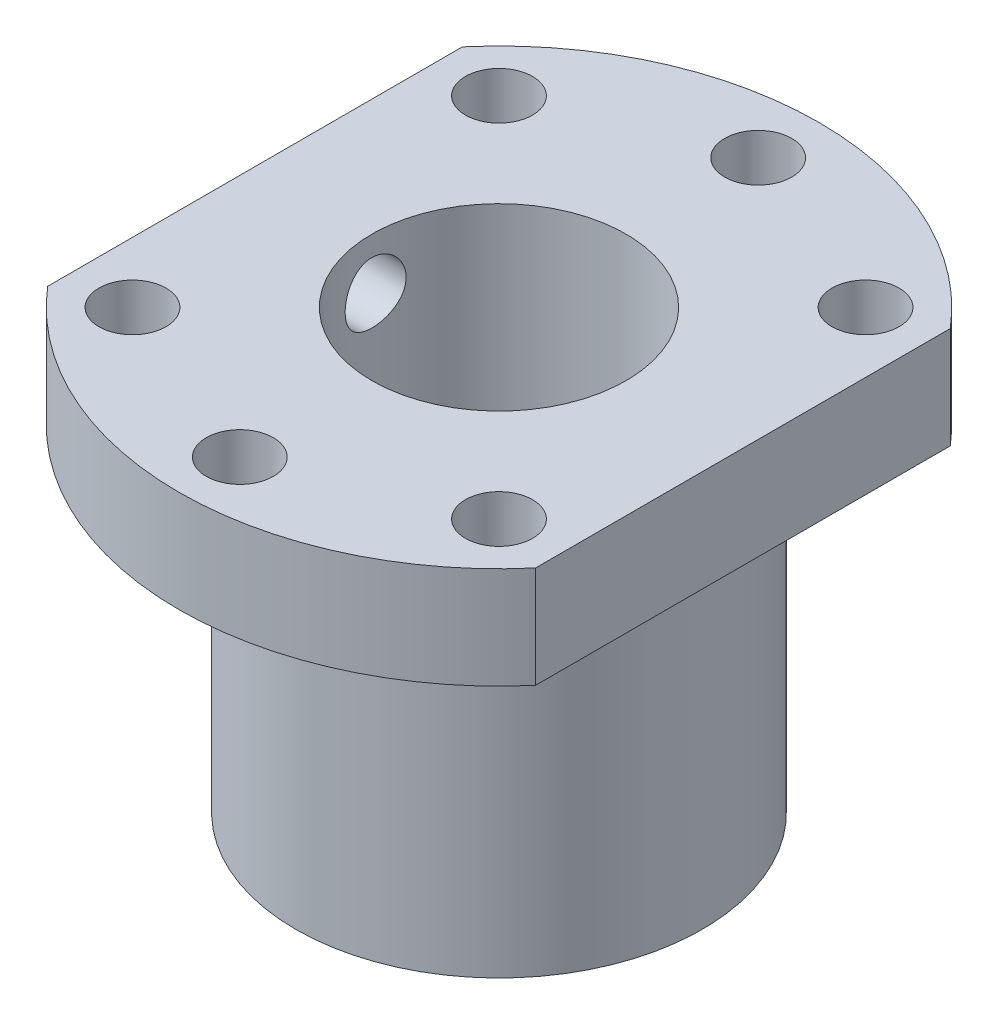
SolidWorks part; units mm, degrees
material "合金钢"
ref_plane "前视基准面" through (0, 0, 0) normal (0, 0, 1) x (1, 0, 0)
ref_plane "上视基准面" through (0, 0, 0) normal (0, 1, 0) x (1, 0, 0)
ref_plane "右视基准面" through (0, 0, 0) normal (1, 0, 0) x (0, 0, -1)
sketch "草图1" plane through (0, 0, 0) normal (0, 1, 0) x (1, 0, 0)
  line L0 (-24, 20.4022) -> (-24, -20.4022)
  line L1 (24, 20.4022) -> (24, -20.4022)
  arc A0 (24, 20.4022) -> (-24, 20.4022) centre (0, 0) ccw
  arc A1 (-24, -20.4022) -> (24, -20.4022) centre (0, 0) ccw
  circle A2 centre (0, 0) radius 12.5
  dimension "D1" = 63
  dimension "D3" = 25
  dimension "D2" = 48
extrude "凸台-拉伸1" add sketch "草图1" against normal blind 10
sketch "草图2" plane through (0, 0, 0) normal (0, 1, 0) x (1, 0, 0)
  circle A0 centre (0, 0) radius 20
  circle A1 centre (0, 0) radius 12.5
  dimension "D1" = 40
  dimension "D2" = 25
extrude "凸台-拉伸2" add sketch "草图2" against normal blind 43
sketch "草图3" plane through (0, 0, 0) normal (0, 1, 0) x (1, 0, 0)
  line L0 (-25.5, 0) -> (25.5, 0) construction
  line L1 (0, 0) -> (-18.0312, 18.0312) construction
  line L2 (0, 0) -> (18.0312, 18.0312) construction
  line L3 (0, 0) -> (0, 25.5) construction
  circle A0 centre (0, 0) radius 25.5 construction
  circle A1 centre (0, 25.5) radius 3.3
  circle A2 centre (-18.0312, 18.0312) radius 3.3
  circle A3 centre (18.0312, 18.0312) radius 3.3
  circle A4 centre (18.0312, -18.0312) radius 3.3
  circle A5 centre (-18.0312, -18.0312) radius 3.3
  circle A6 centre (0, -25.5) radius 3.3
  dimension "D1" = 51
  dimension "D2" = 6.6
  dimension "D3" = 45
  dimension "D4" = 45
extrude "切除-拉伸1" cut sketch "草图3" against normal through all
sketch "草图4" plane through (0, 0, 0) normal (1, 0, 0) x (0, 0, -1)
  circle A0 centre (0, -5) radius 3
  dimension "D1" = 6
  dimension "D2" = 5
extrude "切除-拉伸2" cut sketch "草图4" against normal through all
